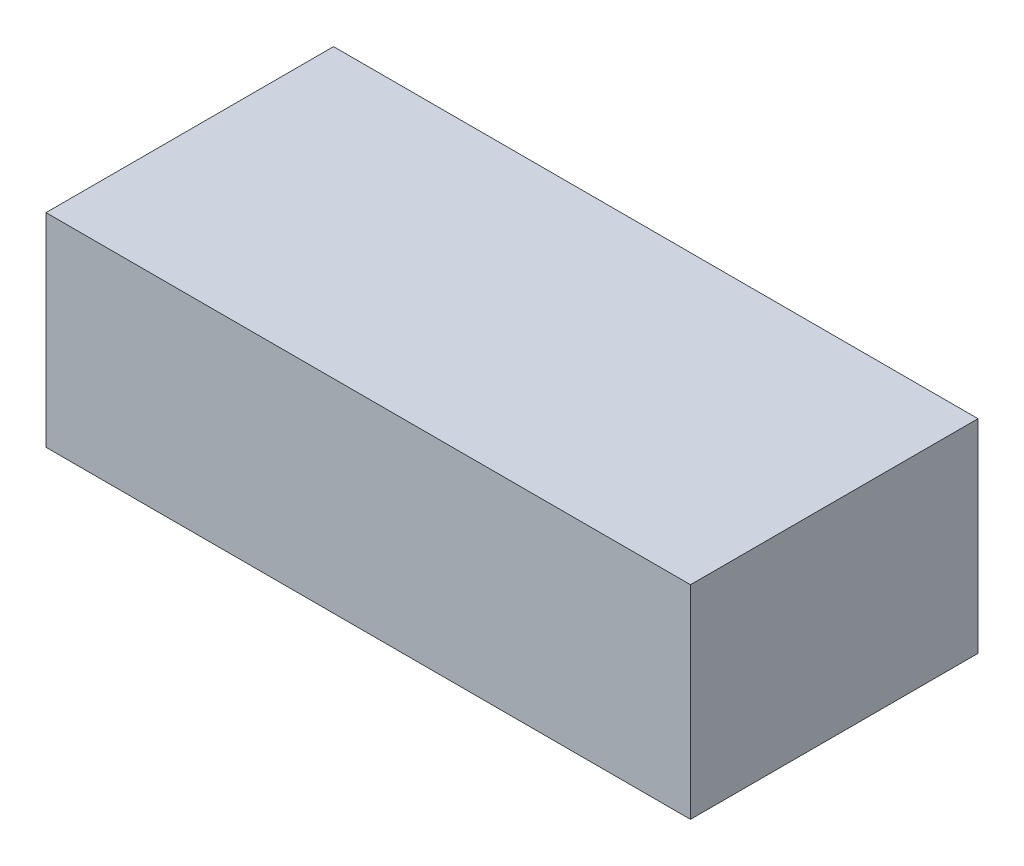
SolidWorks part; units mm, degrees
ref_plane "前视基准面" through (0, 0, 0) normal (0, 0, 1) x (1, 0, 0)
ref_plane "上视基准面" through (0, 0, 0) normal (0, 1, 0) x (1, 0, 0)
ref_plane "右视基准面" through (0, 0, 0) normal (1, 0, 0) x (0, 0, -1)
sketch "草图1" plane through (0, 0, 0) normal (0, 1, 0) x (1, 0, 0)
  line L1 (-32.5, -14.5) -> (32.5, -14.5)
  line L2 (-32.5, -14.5) -> (-32.5, 14.5)
  line L3 (-32.5, 14.5) -> (32.5, 14.5)
  line L4 (32.5, -14.5) -> (32.5, 14.5)
  line L5 (-32.5, -14.5) -> (32.5, 14.5) construction
  line L6 (-32.5, 14.5) -> (32.5, -14.5) construction
  point P0 (0, 0)
  dimension "D1" = 65
  dimension "D2" = 29
extrude "凸台-拉伸1" add sketch "草图1" along normal blind 20.5
